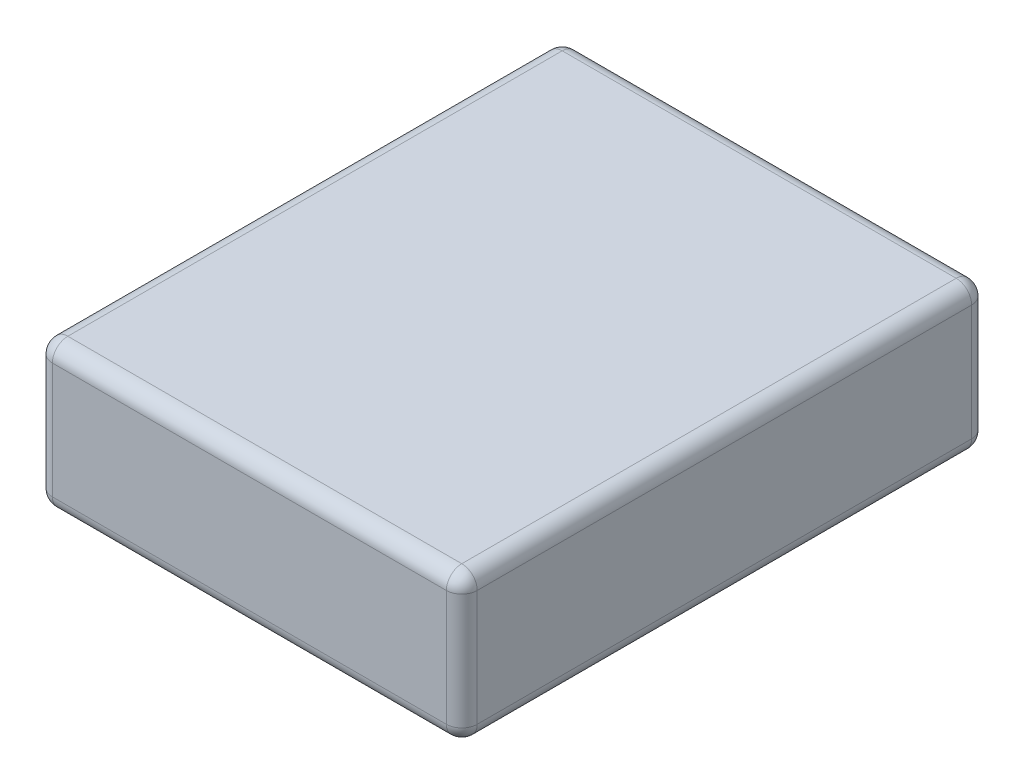
SolidWorks part; units mm, degrees
ref_plane "前视基准面" through (0, 0, 0) normal (0, 0, 1) x (1, 0, 0)
ref_plane "上视基准面" through (0, 0, 0) normal (0, 1, 0) x (1, 0, 0)
ref_plane "右视基准面" through (0, 0, 0) normal (1, 0, 0) x (0, 0, -1)
other "Configuration Table"
sketch "草图1" plane through (0, 0, 0) normal (0, 1, 0) x (1, 0, 0)
  line L1 (27.5, -34) -> (-27.5, -34)
  line L2 (27.5, -34) -> (27.5, 34)
  line L3 (27.5, 34) -> (-27.5, 34)
  line L4 (-27.5, -34) -> (-27.5, 34)
  line L5 (27.5, -34) -> (-27.5, 34) construction
  line L6 (27.5, 34) -> (-27.5, -34) construction
  point P0 (0, 0)
  dimension "D1" = 68
  dimension "D2" = 55
extrude "凸台-拉伸1" add sketch "草图1" along normal blind 19
fillet "圆角1" radius 2 12 edges at (-27.5, 9.5, 34) (27.5, 9.5, 34) (-27.5, 9.5, -34) (27.5, 9.5, -34) (0, 0, -34) (0, 19, -34) (0, 0, 34) (0, 19, 34) (-27.5, 19, 0) (-27.5, 0, 0) (27.5, 0, 0) (27.5, 19, 0)
